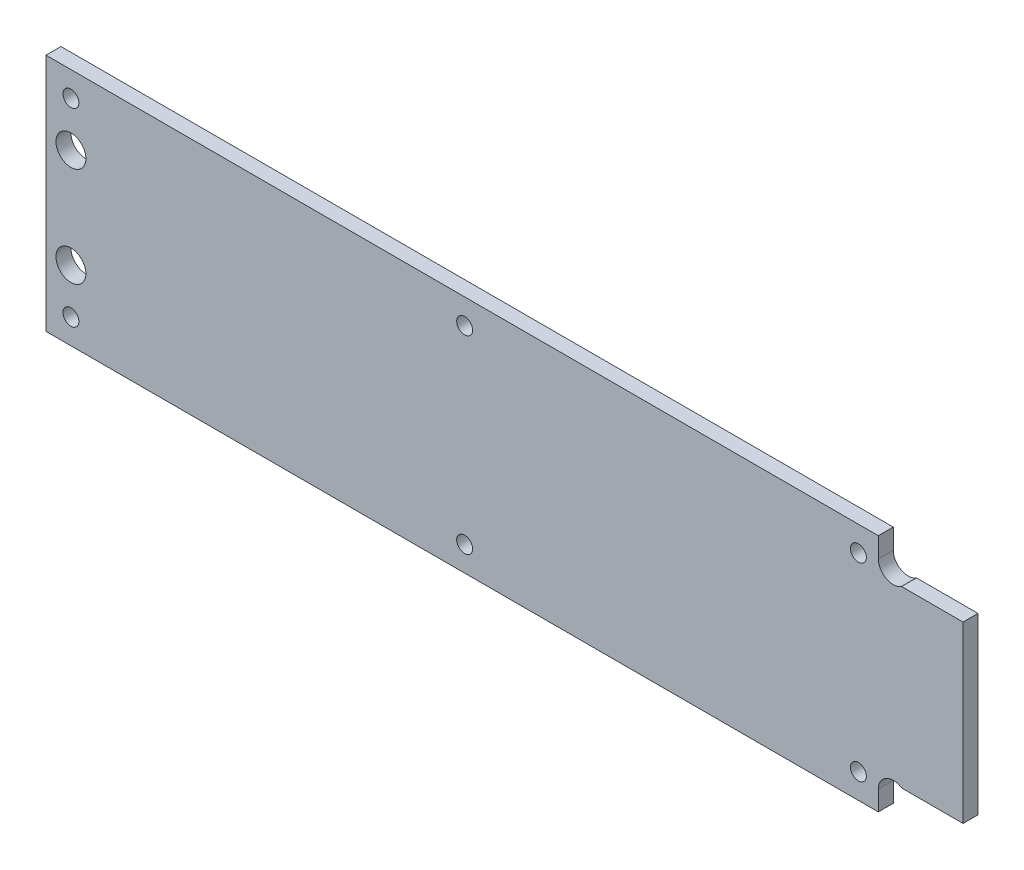
SolidWorks part; units mm, degrees
ref_plane "Top Plane" through (0, 0, 0) normal (0, 0, 1) x (1, 0, 0)
ref_plane "Right Plane" through (0, 0, 0) normal (0, 1, 0) x (1, 0, 0)
ref_plane "Front Plane" through (0, 0, 0) normal (1, 0, 0) x (0, 0, -1)
sketch "Sketch1" plane through (0, 0, 0) normal (0, 0, 1) x (1, 0, 0)
  line L8 (87.6583, -17.5) -> (100, -17.5)
  line L9 (100, -17.5) -> (100, 17.5)
  line L10 (100, 17.5) -> (87.6583, 17.5)
  line L11 (83, 20) -> (83, 24)
  line L12 (83, 24) -> (-84, 24)
  line L13 (-84, 24) -> (-84, -24)
  line L14 (-84, -24) -> (83, -24)
  line L15 (83, -24) -> (83, -20)
  line L16 (87.6583, -17.5) -> (100, -17.5)
  line L17 (100, -17.5) -> (100, 17.5)
  line L18 (100, 17.5) -> (87.6583, 17.5)
  line L19 (83, 20) -> (83, 24)
  line L20 (83, 24) -> (-84, 24)
  line L21 (-84, 24) -> (-84, -24)
  line L22 (-84, -24) -> (83, -24)
  line L23 (83, -24) -> (83, -20)
  line L36 (77, 10) -> (74, 10)
  line L37 (77, 15.5) -> (77, 10)
  line L38 (98, 15.5) -> (77, 15.5)
  line L39 (98, -15.5) -> (98, 15.5)
  line L40 (77, -15.5) -> (98, -15.5)
  line L41 (77, -10) -> (77, -15.5)
  line L42 (74, -10) -> (77, -10)
  line L43 (74, -20) -> (74, -10)
  line L44 (6, -21) -> (73, -21)
  line L45 (5, -19) -> (5, -20)
  line L46 (-5, -20) -> (-5, -19)
  line L47 (-73, -21) -> (-6, -21)
  line L48 (-74, 20) -> (-74, -20)
  line L49 (-6, 21) -> (-73, 21)
  line L50 (-5, 19) -> (-5, 20)
  line L51 (5, 20) -> (5, 19)
  line L52 (73, 21) -> (6, 21)
  line L53 (74, 10) -> (74, 20)
  line L54 (77, 10) -> (74, 10) construction
  line L55 (77, 15.5) -> (77, 10) construction
  line L56 (98, 15.5) -> (77, 15.5) construction
  line L57 (98, -15.5) -> (98, 15.5) construction
  line L58 (77, -15.5) -> (98, -15.5) construction
  line L59 (77, -10) -> (77, -15.5) construction
  line L60 (74, -10) -> (77, -10) construction
  line L61 (74, -20) -> (74, -10) construction
  line L62 (6, -21) -> (73, -21) construction
  line L63 (5, -19) -> (5, -20) construction
  line L64 (-5, -20) -> (-5, -19) construction
  line L65 (-73, -21) -> (-6, -21) construction
  line L66 (-74, 20) -> (-74, -20) construction
  line L67 (-6, 21) -> (-73, 21) construction
  line L68 (-5, 19) -> (-5, 20) construction
  line L69 (5, 20) -> (5, 19) construction
  line L70 (73, 21) -> (6, 21) construction
  line L71 (74, 10) -> (74, 20) construction
  circle A0 centre (-79, -19) radius 2.1 construction
  circle A1 centre (-79, -10) radius 3 construction
  arc A2 (87.6583, -17.5) -> (83, -20) centre (86, -20) ccw
  arc A3 (83, 20) -> (87.6583, 17.5) centre (86, 20) ccw
  arc A4 (87.6583, -17.5) -> (83, -20) centre (86, -20) ccw
  arc A5 (83, 20) -> (87.6583, 17.5) centre (86, 20) ccw
  circle A6 centre (-79, 10) radius 3 construction
  circle A7 centre (-79, 19) radius 2.1 construction
  circle A8 centre (-79, -19) radius 2.1 construction
  circle A9 centre (-79, -10) radius 3
  circle A10 centre (-79, 10) radius 3
  circle A11 centre (-79, 19) radius 2.1 construction
  circle A12 centre (79, -19) radius 2.1 construction
  circle A13 centre (79, 19) radius 2.1 construction
  arc A14 (73, -21) -> (74, -20) centre (73, -20) ccw
  arc A15 (5, -20) -> (6, -21) centre (6, -20) ccw
  arc A16 (5, -19) -> (-5, -19) centre (0, -19) ccw
  arc A17 (-6, -21) -> (-5, -20) centre (-6, -20) ccw
  arc A18 (-74, -20) -> (-73, -21) centre (-73, -20) ccw
  arc A19 (-73, 21) -> (-74, 20) centre (-73, 20) ccw
  arc A20 (-5, 20) -> (-6, 21) centre (-6, 20) ccw
  arc A21 (-5, 19) -> (5, 19) centre (0, 19) ccw
  arc A22 (6, 21) -> (5, 20) centre (6, 20) ccw
  arc A23 (74, 20) -> (73, 21) centre (73, 20) ccw
  arc A24 (73, -21) -> (74, -20) centre (73, -20) ccw construction
  arc A25 (5, -20) -> (6, -21) centre (6, -20) ccw construction
  arc A26 (5, -19) -> (-5, -19) centre (0, -19) ccw construction
  arc A27 (-6, -21) -> (-5, -20) centre (-6, -20) ccw construction
  arc A28 (-74, -20) -> (-73, -21) centre (-73, -20) ccw construction
  arc A29 (-73, 21) -> (-74, 20) centre (-73, 20) ccw construction
  arc A30 (-5, 20) -> (-6, 21) centre (-6, 20) ccw construction
  arc A31 (-5, 19) -> (5, 19) centre (0, 19) ccw construction
  arc A32 (6, 21) -> (5, 20) centre (6, 20) ccw construction
  arc A33 (74, 20) -> (73, 21) centre (73, 20) ccw construction
  circle A34 centre (0, -19) radius 2.1 construction
  circle A35 centre (0, 19) radius 2.1 construction
  circle A36 centre (79, -19) radius 2.1 construction
  circle A37 centre (79, 19) radius 2.1 construction
  circle A38 centre (0, -19) radius 2.1 construction
  circle A39 centre (0, 19) radius 2.1 construction
  dimension "D1" = 0
  dimension "D2" = 0
extrude "Boss-Extrude1" add sketch "Sketch1" along normal blind 3
sketch "Sketch2" plane through (0, 0, 0) normal (0, 0, -1) x (-1, 0, 0)
  line L18 (-7.2938, 18.7) -> (-71.7, 18.7)
  line L19 (-71.7, 18.7) -> (-71.7, 7.7)
  line L20 (-71.7, 7.7) -> (-79.3, 7.7)
  line L21 (-79.3, 7.7) -> (-79.3, 13.2)
  line L22 (-79.3, 13.2) -> (-95.7, 13.2)
  line L23 (-95.7, 13.2) -> (-95.7, -13.2)
  line L24 (-95.7, -13.2) -> (-79.3, -13.2)
  line L25 (-79.3, -13.2) -> (-79.3, -7.7)
  line L26 (-79.3, -7.7) -> (-71.7, -7.7)
  line L27 (-71.7, -7.7) -> (-71.7, -18.7)
  line L28 (-71.7, -18.7) -> (-7.2938, -18.7)
  line L29 (-7.2938, -18.7) -> (-7.2938, -18.7)
  line L30 (7.2938, -18.7) -> (7.2938, -18.7)
  line L31 (7.2938, -18.7) -> (71.7, -18.7)
  line L32 (71.7, -18.7) -> (71.7, 18.7)
  line L33 (71.7, 18.7) -> (7.2938, 18.7)
  line L34 (7.2938, 18.7) -> (7.2938, 18.7)
  line L35 (-7.2938, 18.7) -> (-7.2938, 18.7)
  line L36 (-73.7, 20) -> (-73.7, 9.7)
  line L37 (-73.7, 9.7) -> (-77.3, 9.7)
  line L38 (-77.3, 9.7) -> (-77.3, 15.2)
  line L39 (-77.3, 15.2) -> (-97.7, 15.2)
  line L40 (-97.7, 15.2) -> (-97.7, -15.2)
  line L41 (-97.7, -15.2) -> (-77.3, -15.2)
  line L42 (-77.3, -15.2) -> (-77.3, -9.7)
  line L43 (-77.3, -9.7) -> (-73.7, -9.7)
  line L44 (-73.7, -9.7) -> (-73.7, -20)
  line L45 (-73, -20.7) -> (-6, -20.7)
  line L46 (-5.3, -20) -> (-5.3, -19)
  line L47 (5.3, -19) -> (5.3, -20)
  line L48 (6, -20.7) -> (73, -20.7)
  line L49 (73.7, -20) -> (73.7, 20)
  line L50 (73, 20.7) -> (6, 20.7)
  line L51 (5.3, 20) -> (5.3, 19)
  line L52 (-5.3, 19) -> (-5.3, 20)
  line L53 (-6, 20.7) -> (-73, 20.7)
  line L54 (-73.7, 20) -> (-73.7, 9.7)
  line L55 (-73.7, 9.7) -> (-77.3, 9.7)
  line L56 (-77.3, 9.7) -> (-77.3, 15.2)
  line L57 (-77.3, 15.2) -> (-97.7, 15.2)
  line L58 (-97.7, 15.2) -> (-97.7, -15.2)
  line L59 (-97.7, -15.2) -> (-77.3, -15.2)
  line L60 (-77.3, -15.2) -> (-77.3, -9.7)
  line L61 (-77.3, -9.7) -> (-73.7, -9.7)
  line L62 (-73.7, -9.7) -> (-73.7, -20)
  line L63 (-73, -20.7) -> (-6, -20.7)
  line L64 (-5.3, -20) -> (-5.3, -19)
  line L65 (5.3, -19) -> (5.3, -20)
  line L66 (6, -20.7) -> (73, -20.7)
  line L67 (73.7, -20) -> (73.7, 20)
  line L68 (73, 20.7) -> (6, 20.7)
  line L69 (5.3, 20) -> (5.3, 19)
  line L70 (-5.3, 19) -> (-5.3, 20)
  line L71 (-6, 20.7) -> (-73, 20.7)
  arc A10 (-71.7, 18.7) -> (-71.7, 18.7) centre (-71.7, 18.7) ccw
  arc A11 (-71.7, -18.7) -> (-71.7, -18.7) centre (-71.7, -18.7) ccw
  arc A12 (-7.2938, -18.7) -> (-7.2938, -18.7) centre (-7.2938, -18.7) ccw
  arc A13 (7.2938, -18.7) -> (-7.2938, -18.7) centre (0, -19) ccw
  arc A14 (7.2938, -18.7) -> (7.2938, -18.7) centre (7.2938, -18.7) ccw
  arc A15 (71.7, -18.7) -> (71.7, -18.7) centre (71.7, -18.7) ccw
  arc A16 (71.7, 18.7) -> (71.7, 18.7) centre (71.7, 18.7) ccw
  arc A17 (7.2938, 18.7) -> (7.2938, 18.7) centre (7.2938, 18.7) ccw
  arc A18 (-7.2938, 18.7) -> (7.2938, 18.7) centre (0, 19) ccw
  arc A19 (-7.2938, 18.7) -> (-7.2938, 18.7) centre (-7.2938, 18.7) ccw
  arc A20 (-73, 20.7) -> (-73.7, 20) centre (-73, 20) ccw
  arc A21 (-73.7, -20) -> (-73, -20.7) centre (-73, -20) ccw
  arc A22 (-6, -20.7) -> (-5.3, -20) centre (-6, -20) ccw
  arc A23 (5.3, -19) -> (-5.3, -19) centre (0, -19) ccw
  arc A24 (5.3, -20) -> (6, -20.7) centre (6, -20) ccw
  arc A25 (73, -20.7) -> (73.7, -20) centre (73, -20) ccw
  arc A26 (73.7, 20) -> (73, 20.7) centre (73, 20) ccw
  arc A27 (6, 20.7) -> (5.3, 20) centre (6, 20) ccw
  arc A28 (-5.3, 19) -> (5.3, 19) centre (0, 19) ccw
  arc A29 (-5.3, 20) -> (-6, 20.7) centre (-6, 20) ccw
  arc A30 (-73, 20.7) -> (-73.7, 20) centre (-73, 20) ccw
  arc A31 (-73.7, -20) -> (-73, -20.7) centre (-73, -20) ccw
  arc A32 (-6, -20.7) -> (-5.3, -20) centre (-6, -20) ccw
  arc A33 (5.3, -19) -> (-5.3, -19) centre (0, -19) ccw
  arc A34 (5.3, -20) -> (6, -20.7) centre (6, -20) ccw
  arc A35 (73, -20.7) -> (73.7, -20) centre (73, -20) ccw
  arc A36 (73.7, 20) -> (73, 20.7) centre (73, 20) ccw
  arc A37 (6, 20.7) -> (5.3, 20) centre (6, 20) ccw
  arc A38 (-5.3, 19) -> (5.3, 19) centre (0, 19) ccw
  arc A39 (-5.3, 20) -> (-6, 20.7) centre (-6, 20) ccw
  dimension "D1" = 0.3
  dimension "D2" = 2
extrude "Boss-Extrude2" add sketch "Sketch2" along normal blind 2
chamfer "Chamfer1" distance 0.5 angle 45 28 edges at (39.5, 20.7, -2) (5.505, 20.495, -2) (5.3, 19.5, -2) (0, 13.7, -2) (-5.3, 19.5, -2) (-5.505, 20.495, -2) (-39.5, 20.7, -2) (-73.495, 20.495, -2) (-73.7, 0, -2) (-73.495, -20.495, -2) (-39.5, -20.7, -2) (-5.505, -20.495, -2) (-5.3, -19.5, -2) (0, -13.7, -2) (5.3, -19.5, -2) (5.505, -20.495, -2) (39.5, -20.7, -2) (73.495, -20.495, -2) (73.7, -14.85, -2) (75.5, -9.7, -2) (77.3, -12.45, -2) (87.5, -15.2, -2) (97.7, 0, -2) (87.5, 15.2, -2) (77.3, 12.45, -2) (75.5, 9.7, -2) (73.7, 14.85, -2) (73.495, 20.495, -2)
fillet "Fillet1" radius 1 16 edges at (-71.7, 0, 0) (-39.4969, -18.7, 0) (0, -11.7, 0) (39.4969, -18.7, 0) (71.7, -13.2, 0) (75.5, -7.7, 0) (79.3, -10.45, 0) (87.5, -13.2, 0) (95.7, 0, 0) (87.5, 13.2, 0) (79.3, 10.45, 0) (75.5, 7.7, 0) (71.7, 13.2, 0) (39.4969, 18.7, 0) (0, 11.7, 0) (-39.4969, 18.7, 0)
sketch "Sketch3" plane through (0, 0, 3) normal (0, 0, 1) x (1, 0, 0)
  circle A0 centre (-79, 19) radius 1.6
  circle A1 centre (-79, -19) radius 1.6
  circle A2 centre (79, 19) radius 1.6
  circle A3 centre (79, -19) radius 1.6
  circle A4 centre (0, 19) radius 1.6
  circle A5 centre (0, -19) radius 1.6
  dimension "D1" = 3.2
extrude "Cut-Extrude1" cut sketch "Sketch3" against normal through all
